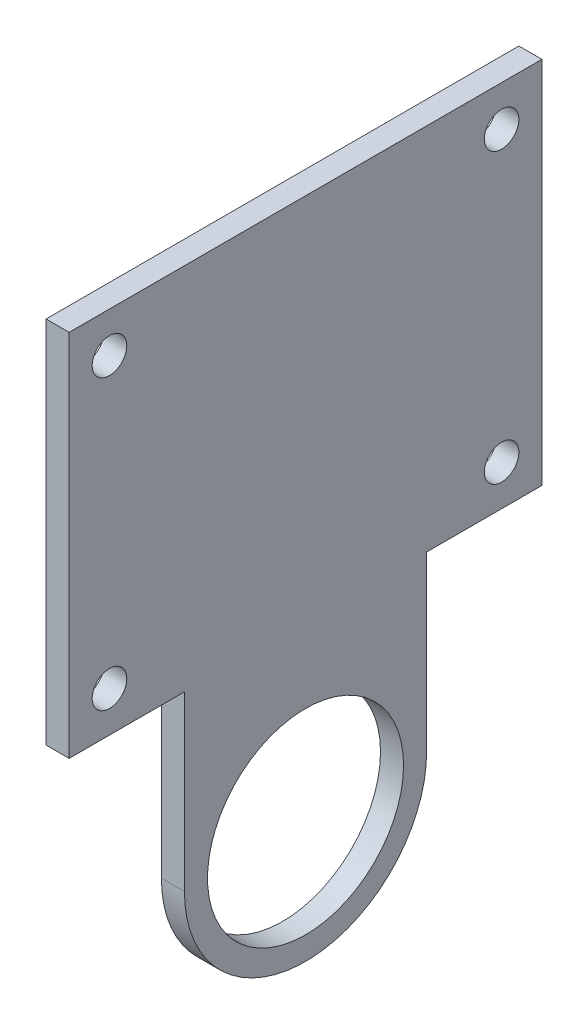
SolidWorks part; units mm, degrees
ref_plane "前视基准面" through (0, 0, 0) normal (0, 0, 1) x (1, 0, 0)
ref_plane "上视基准面" through (0, 0, 0) normal (0, 1, 0) x (1, 0, 0)
ref_plane "右视基准面" through (0, 0, 0) normal (1, 0, 0) x (0, 0, -1)
sketch "草图1" plane through (0, 0, 0) normal (1, 0, 0) x (0, 0, -1)
  line L0 (-10.5, 0) -> (-10.5, 15)
  line L1 (-10.5, 15) -> (-20.5, 15)
  line L2 (-20.5, 47) -> (-20.5, 15)
  line L3 (-20.5, 47) -> (20.5, 47)
  line L4 (20.5, 47) -> (20.5, 15)
  line L5 (20.5, 15) -> (10.5, 15)
  line L6 (10.5, 15) -> (10.5, 0)
  arc A0 (10.5, 0) -> (-10.5, 0) centre (0, 0) cw
  circle A1 centre (0, 0) radius 8.5
  circle A2 centre (-17, 43.5) radius 1.5
  circle A3 centre (17, 43.5) radius 1.5
  circle A4 centre (-17, 18.5) radius 1.5
  circle A5 centre (17, 18.5) radius 1.5
  dimension "D1" = 15
  dimension "D3" = 17
  dimension "D4" = 10.5
  dimension "D2" = 10
  dimension "D5" = 15
  dimension "D6" = 10
  dimension "D7" = 32
  dimension "D8" = 2
  dimension "D9" = 2
  dimension "D10" = 2
  dimension "D11" = 21
extrude "凸台-拉伸1" add sketch "草图1" along normal blind 2
